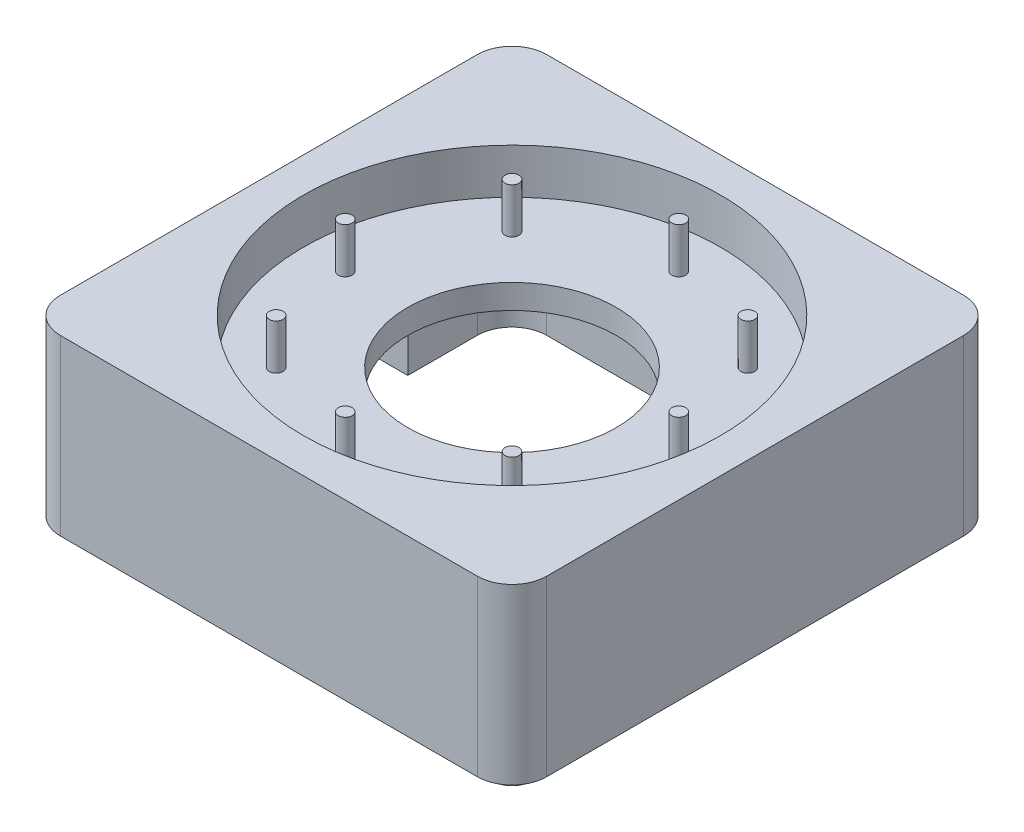
SolidWorks part; units mm, degrees
ref_plane "Front Plane" through (0, 0, 0) normal (0, 0, 1) x (1, 0, 0)
ref_plane "Top Plane" through (0, 0, 0) normal (0, 1, 0) x (1, 0, 0)
ref_plane "Right Plane" through (0, 0, 0) normal (1, 0, 0) x (0, 0, -1)
sketch "Sketch1" plane through (0, 0, 0) normal (0, 1, 0) x (1, 0, 0)
  line L1 (-57.1487, 55.4582) -> (62.8513, 55.4582)
  line L2 (-67.1487, 45.4582) -> (-67.1487, -74.5418)
  line L3 (-57.1487, -84.5418) -> (62.8513, -84.5418)
  line L4 (72.8513, 45.4582) -> (72.8513, -74.5418)
  arc A0 (-67.1487, -74.5418) -> (-57.1487, -84.5418) centre (-57.1487, -74.5418) ccw
  arc A1 (62.8513, -84.5418) -> (72.8513, -74.5418) centre (62.8513, -74.5418) ccw
  arc A2 (62.8513, 55.4582) -> (72.8513, 45.4582) centre (62.8513, 45.4582) cw
  arc A3 (-57.1487, 55.4582) -> (-67.1487, 45.4582) centre (-57.1487, 45.4582) ccw
  point P8 (72.8513, -84.5418)
  point P11 (72.8513, 55.4582)
  point P14 (-67.1487, 55.4582)
  dimension "D3" = 10
  dimension "D1" = 140
  dimension "D2" = 140
extrude "Boss-Extrude1" add sketch "Sketch1" along normal blind 50
sketch "Sketch2" plane through (0, 50, 0) normal (0, 1, 0) x (1, 0, 0)
  line L0 (72.8513, -74.5418) -> (72.8513, 45.4582) construction
  line L2 (62.8513, 55.4582) -> (-57.1487, 55.4582) construction
  circle A0 centre (2.8513, -14.5418) radius 60
  dimension "D1" = 70
  dimension "D2" = 70
extrude "Cut-Extrude1" cut sketch "Sketch2" against normal blind 13
sketch "Sketch3" plane through (0, 37, 0) normal (0, 1, 0) x (1, 0, 0)
  circle A0 centre (2.8513, -14.5418) radius 10
  circle A1 centre (2.8513, -14.5418) radius 60 construction
  dimension "D1" = 0
extrude "Cut-Extrude2" cut sketch "Sketch3" against normal blind 50
sketch "Sketch4" plane through (0, 37, 0) normal (0, 1, 0) x (1, 0, 0)
  line L0 (72.8513, -74.5418) -> (72.8513, 45.4582) construction
  circle A0 centre (2.8513, 33.4582) radius 2
  circle A1 centre (2.8513, -14.5418) radius 60 construction
  circle A2 centre (36.7924, 19.3994) radius 2
  circle A3 centre (50.8513, -14.5418) radius 2
  circle A4 centre (36.7924, -48.4829) radius 2
  circle A5 centre (2.8513, -62.5418) radius 2
  circle A6 centre (-31.0898, -48.4829) radius 2
  circle A7 centre (-45.1487, -14.5418) radius 2
  circle A8 centre (-31.0898, 19.3994) radius 2
  point P23 (2.8513, -14.5418)
  dimension "D1" = 48
  dimension "D2" = 70
  dimension "D3" = 8
extrude "Boss-Extrude2" add sketch "Sketch4" along normal blind 13
sketch "Sketch5" plane through (0, 0, 0) normal (0, -1, 0) x (1, 0, 0)
  line L0 (62.8513, -55.4582) -> (-57.1487, -55.4582) construction
  line L1 (-37.1487, 64.5418) -> (42.8513, 64.5418)
  line L2 (-47.1487, 54.5418) -> (-47.1487, -25.4582)
  line L3 (-37.1487, -35.4582) -> (42.8513, -35.4582)
  line L4 (52.8513, 54.5418) -> (52.8513, -25.4582)
  line L5 (-67.1487, -45.4582) -> (-67.1487, 74.5418) construction
  arc A0 (-47.1487, -25.4582) -> (-37.1487, -35.4582) centre (-37.1487, -25.4582) ccw
  arc A1 (42.8513, -35.4582) -> (52.8513, -25.4582) centre (42.8513, -25.4582) ccw
  arc A2 (42.8513, 64.5418) -> (52.8513, 54.5418) centre (42.8513, 54.5418) cw
  arc A3 (-37.1487, 64.5418) -> (-47.1487, 54.5418) centre (-37.1487, 54.5418) ccw
  point P12 (52.8513, -35.4582)
  point P15 (52.8513, 64.5418)
  point P18 (-47.1487, 64.5418)
  dimension "D5" = 10
  dimension "D1" = 100
  dimension "D2" = 100
  dimension "D3" = 20
  dimension "D4" = 20
extrude "Cut-Extrude3" cut sketch "Sketch5" against normal blind 30
sketch "Sketch6" plane through (0, 0, 0) normal (0, -1, 0) x (1, 0, 0)
  line L0 (-67.1487, -45.4582) -> (-67.1487, 74.5418) construction
  line L1 (-57.1487, 84.5418) -> (62.8513, 84.5418) construction
  circle A0 centre (-57.1487, 74.5418) radius 6
  circle A1 centre (62.8513, 74.5418) radius 6
  circle A2 centre (62.8513, -45.4582) radius 6
  circle A3 centre (-57.1487, -45.4582) radius 6
  dimension "D1" = 10
  dimension "D2" = 10
  dimension "D3" = 2
  dimension "D4" = 2
extrude "Boss-Extrude4" add sketch "Sketch6" along normal blind 3 contours A0 | A1 | A3 | A2
sketch "Sketch7" plane through (0, 37, 0) normal (0, 1, 0) x (1, 0, 0)
  circle A0 centre (2.8513, -14.5418) radius 30
extrude "Cut-Extrude4" cut sketch "Sketch7" against normal blind 40
sketch "Sketch8" plane through (-67.1487, 0, 0) normal (-1, 0, 0) x (0, 0, 1)
  line L6 (-45.4582, 0) -> (74.5418, 0) construction
  line L7 (-5.4582, 0) -> (34.5418, 0)
  line L8 (-5.4582, 0) -> (-5.4582, 12)
  line L9 (-2.4582, 15) -> (31.5418, 15)
  line L10 (34.5418, 0) -> (34.5418, 12)
  line L11 (74.5418, 50) -> (74.5418, 0) construction
  line L12 (-45.4582, 50) -> (-45.4582, 0) construction
  arc A4 (31.5418, 15) -> (34.5418, 12) centre (31.5418, 12) cw
  arc A5 (-5.4582, 12) -> (-2.4582, 15) centre (-2.4582, 12) cw
  point P6 (-4.6023, 17.6611)
  point P11 (35.3977, 17.6611)
  point P12 (34.5418, 15)
  point P14 (35.3977, 32.6611)
  point P16 (-5.4582, 15)
  dimension "D3" = 40
  dimension "D4" = 3
  dimension "D1" = 40
  dimension "D2" = 15
extrude "Cut-Extrude5" cut sketch "Sketch8" against normal blind 25
